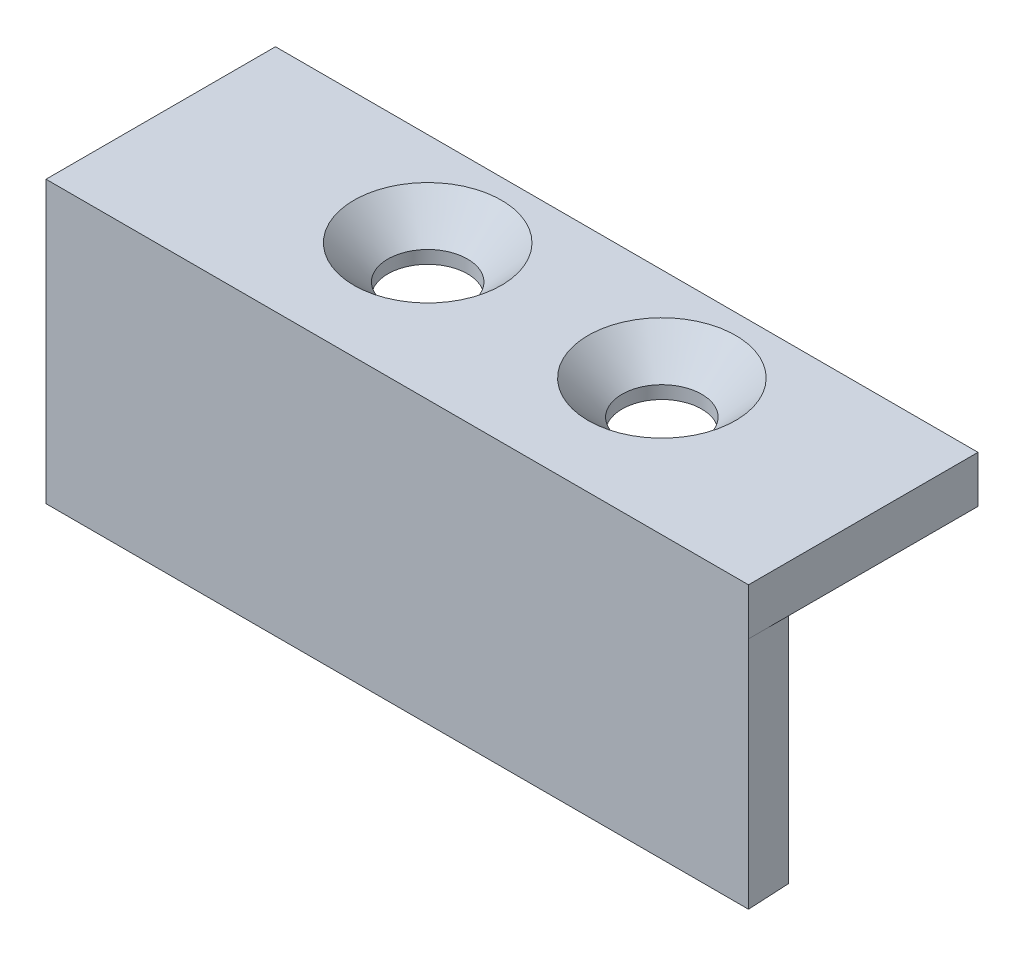
SolidWorks part; units mm, degrees
ref_plane "Front Plane" through (0, 0, 0) normal (0, 0, 1) x (1, 0, 0)
ref_plane "Top Plane" through (0, 0, 0) normal (0, 1, 0) x (1, 0, 0)
ref_plane "Right Plane" through (0, 0, 0) normal (1, 0, 0) x (0, 0, -1)
sketch "Skizze1" plane through (0, 0, 0) normal (0, 1, 0) x (1, 0, 0)
  line L1 (-10, 13) -> (20, 13)
  line L2 (-10, 13) -> (-10, 3.2)
  line L3 (-10, 3.2) -> (20, 3.2)
  line L4 (20, 13) -> (20, 3.2)
  dimension "D1" = 30
  dimension "D2" = 9.8
extrude "Aufsatz-Linear austragen1" add sketch "Skizze1" along normal blind 2
hole_wizard "Formsenkung für M3 Linsensenkschraube mit Schlitz1" positions "Skizze7" profile "Skizze8" countersink size "M3" standard "DIN"
sketch "Skizze7" plane through (0, 2, 0) normal (0, 1, 0) x (1, 0, 0)
  line L0 (20, 9) -> (-10, 9) construction
  line L1 (20, 3.2) -> (20, 13) construction
  line L2 (-10, 13) -> (-10, 3.2) construction
  line L4 (20, 13) -> (-10, 13) construction
  line L5 (5.5, 13) -> (5.5, -13) construction
  point P0 (0.5, 9)
  point P2 (10.5, 9)
  dimension "D1" = 4
  dimension "D2" = 10
  dimension "D3" = 14.5
sketch "Skizze8" plane through (0.5, 2, -9) normal (1, 0, 0) x (0, 0, 1)
  line L0 (0, 0) -> (0, 9.5215)
  line L1 (0, 9.5215) -> (1.7, 8.5)
  line L2 (1.7, 8.5) -> (1.7, 1.45)
  line L3 (1.7, 1.45) -> (3.15, 0)
  line L5 (3.15, 0) -> (0, 0)
  line L6 (-1.7, 1.45) -> (-3.15, 0) construction
  line L10 (0, 9.5215) -> (-1.7, 8.5) construction
  line L11 (0, -6.35) -> (0, 107.95) construction
  dimension "Bohrerdurchmesser" = 3.4
  dimension "Bohrungstiefe" = 8.5
  dimension "Senkdurchmesser (Oben)" = 6.3
  dimension "Senkwinkel (Oben)" = 90
  dimension "Spitzenwinkel" = 118
sketch "Skizze13" plane through (0, 0, 0) normal (0, -1, 0) x (1, 0, 0)
  line L0 (-10, -3.2) -> (-10, -4.9976)
  line L2 (-10, -13) -> (-10, -3.2) construction
  line L5 (-10, -3.2) -> (20, -3.2)
  line L7 (20, -3.2) -> (20, -13) construction
  line L9 (20, -3.2) -> (19.9064, -4.9976)
  line L10 (19.9064, -4.9976) -> (-10, -4.9976)
  dimension "D1" = 1.7976
  dimension "D2" = 1.8
extrude "Aufsatz-Linear austragen2" add sketch "Skizze13" along normal blind 10
